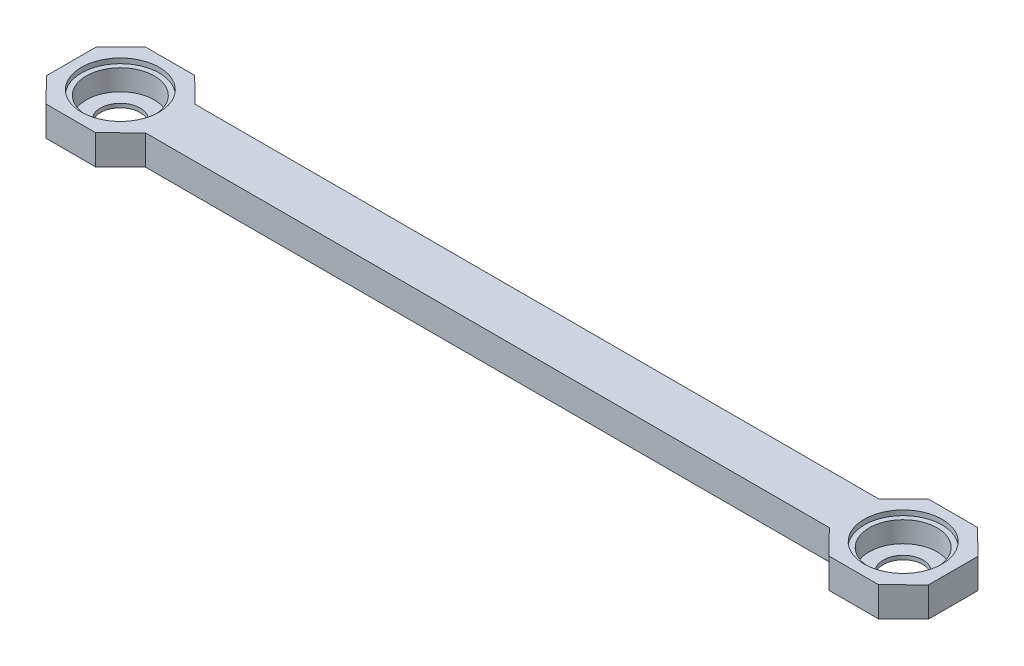
SolidWorks part; units mm, degrees
ref_plane "前视基准面" through (0, 0, 0) normal (0, 0, 1) x (1, 0, 0)
ref_plane "上视基准面" through (0, 0, 0) normal (0, 1, 0) x (1, 0, 0)
ref_plane "右视基准面" through (0, 0, 0) normal (1, 0, 0) x (0, 0, -1)
sketch "草图1" plane through (0, 0, 0) normal (0, 1, 0) x (1, 0, 0)
  line L0 (-56.1468, 0) -> (96.1142, 0) construction
  line L9 (-65.2623, 5) -> (-70.3633, 10)
  line L10 (-70.3633, 10) -> (-80.3633, 10)
  line L19 (-80.3633, 10) -> (-85.2623, 5)
  line L20 (-85.2623, 5) -> (-85.2623, -5)
  line L23 (72.7377, 5) -> (77.6367, 10)
  line L24 (77.6367, 10) -> (87.6367, 10)
  line L25 (87.6367, 10) -> (92.7398, 5)
  line L26 (92.7398, 5) -> (92.7398, -5)
  line L27 (-75.3633, 10) -> (-75.3633, -5.1974) construction
  line L28 (82.6367, 10) -> (82.6367, -7.8958) construction
  line L29 (-65.2623, -5) -> (-70.3633, -10)
  line L30 (-70.3633, -10) -> (-80.3633, -10)
  line L31 (-80.3633, -10) -> (-85.2623, -5)
  line L32 (87.6367, -10) -> (92.7398, -5)
  line L33 (77.6367, -10) -> (87.6367, -10)
  line L34 (72.7377, -5) -> (77.6367, -10)
  line L35 (-65.2623, 5) -> (72.7377, 5)
  line L36 (72.7377, -5) -> (-65.2623, -5)
  circle A0 centre (-75.3633, 0) radius 4
  circle A2 centre (82.6367, 0) radius 4
  point P18 (-27.2623, 0)
  point P24 (-85.2623, 0)
  point P25 (92.7398, 0)
  point P28 (72.7377, 0)
  dimension "D1" = 158
  dimension "D2" = 10
  dimension "D11" = 8
  dimension "D12" = 8
  dimension "D3" = 5
  dimension "D4" = 20.0021
  dimension "D5" = 10
  dimension "D6" = 7
  dimension "D7" = 10
  dimension "D8" = 7
  dimension "D9" = 10
  dimension "D10" = 5
  dimension "D13" = 20
extrude "凸台-拉伸1" add sketch "草图1" along normal blind 6
sketch "草图2" plane through (0, 6, 0) normal (0, 1, 0) x (1, 0, 0)
  circle A0 centre (82.6367, 0) radius 6.85
  circle A1 centre (-75.3633, 0) radius 6.85
  dimension "D1" = 13.7
extrude "切除-拉伸1" cut sketch "草图2" against normal blind 5.2
sketch "草图3" plane through (0, 6, 0) normal (0, 1, 0) x (1, 0, 0)
  circle A0 centre (82.6367, 0) radius 7.85
  circle A1 centre (-75.3633, 0) radius 7.85
  dimension "D1" = 15.7
extrude "切除-拉伸2" cut sketch "草图3" against normal blind 1
